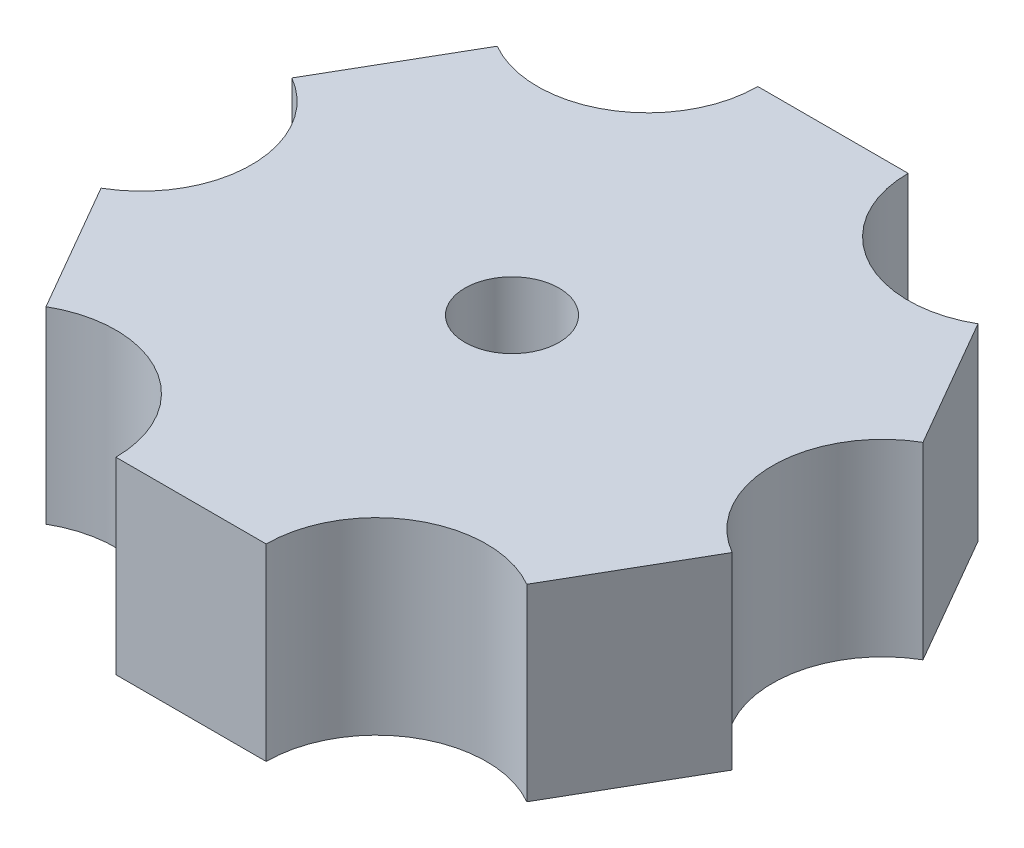
SolidWorks part; units mm, degrees
ref_plane "Front Plane" through (0, 0, 0) normal (0, 0, 1) x (1, 0, 0)
ref_plane "Top Plane" through (0, 0, 0) normal (0, 1, 0) x (1, 0, 0)
ref_plane "Right Plane" through (0, 0, 0) normal (1, 0, 0) x (0, 0, -1)
sketch "Sketch1" plane through (0, 0, 0) normal (0, 1, 0) x (1, 0, 0)
  line L0 (0, 35) -> (0, -35) construction
  line L1 (-35, 0) -> (35, 0) construction
  line L2 (-7.9799, 34.0782) -> (7.9799, 34.0782)
  line L3 (-30.3109, -17.5) -> (30.3109, 17.5) construction
  line L4 (30.3109, -17.5) -> (-30.3109, 17.5) construction
  line L5 (25.5226, 23.9499) -> (33.5025, 10.1283)
  line L6 (33.5025, -10.1283) -> (25.5226, -23.9499)
  line L7 (7.9799, -34.0782) -> (-7.9799, -34.0782)
  line L8 (-33.5025, -10.1283) -> (-25.5226, -23.9499)
  line L9 (-25.5226, 23.9499) -> (-33.5025, 10.1283)
  circle A0 centre (0, 0) radius 35 construction
  arc A1 (7.9799, 34.0782) -> (25.5226, 23.9499) centre (19.675, 34.0782) ccw
  arc A2 (33.5025, -10.1283) -> (33.5025, 10.1283) centre (39.3501, 0) cw
  arc A3 (7.9799, -34.0782) -> (25.5226, -23.9499) centre (19.675, -34.0782) cw
  arc A4 (-7.9799, -34.0782) -> (-25.5226, -23.9499) centre (-19.675, -34.0782) ccw
  arc A5 (-33.5025, -10.1283) -> (-33.5025, 10.1283) centre (-39.3501, 0) ccw
  arc A6 (-7.9799, 34.0782) -> (-25.5226, 23.9499) centre (-19.675, 34.0782) cw
  circle A7 centre (0, 0) radius 5
  point P13 (0, 0)
  dimension "D1" = 70
  dimension "D4" = 10
  dimension "D2" = 60
  dimension "D3" = 60
extrude "Boss-Extrude1" add sketch "Sketch1" along normal blind 20
